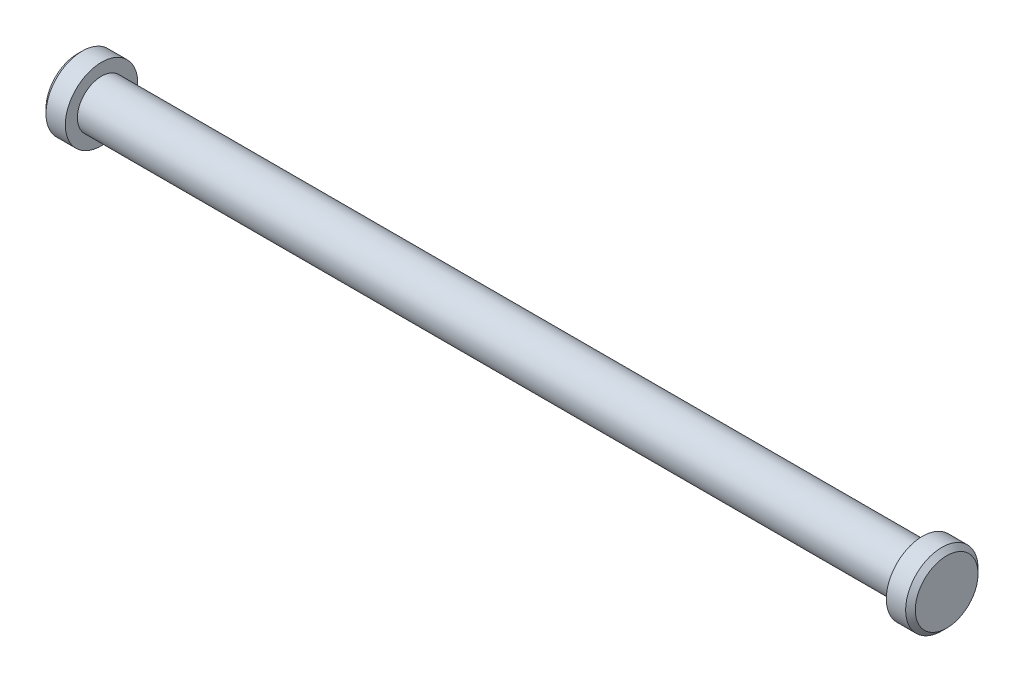
SolidWorks part; units mm, degrees
ref_plane "Front Plane" through (0, 0, 0) normal (0, 0, 1) x (1, 0, 0)
ref_plane "Top Plane" through (0, 0, 0) normal (0, 1, 0) x (1, 0, 0)
ref_plane "Right Plane" through (0, 0, 0) normal (1, 0, 0) x (0, 0, -1)
other "Configuration Table"
sketch "Sketch1" plane through (0, 0, 0) normal (0, 0, 1) x (1, 0, 0)
  line L0 (-22.86, 0) -> (22.86, 0) construction
  line L1 (-22.86, 0) -> (-22.86, 1.905)
  line L2 (-22.86, 1.905) -> (-21.59, 1.905)
  line L3 (-21.59, 1.905) -> (-21.59, 1.27)
  line L4 (-21.59, 1.27) -> (21.59, 1.27)
  line L5 (21.59, 1.27) -> (21.59, 1.905)
  line L6 (21.59, 1.905) -> (22.86, 1.905)
  line L7 (22.86, 1.905) -> (22.86, 0)
  line L8 (-22.86, 0) -> (22.86, 0)
  dimension "D1" = 43.18
  dimension "D2" = 2.54
  dimension "D3" = 3.81
  dimension "D4" = 1.27
revolve "Revolve1" add sketch "Sketch1" angle 360 about L0
chamfer "Chamfer1" distance 0.254 angle 45 2 edges at (-22.86, 0, 1.905) (22.86, 0, 1.905)
scale "Scale1" scale about centroid uniform scaling yes scale factor 1.5
